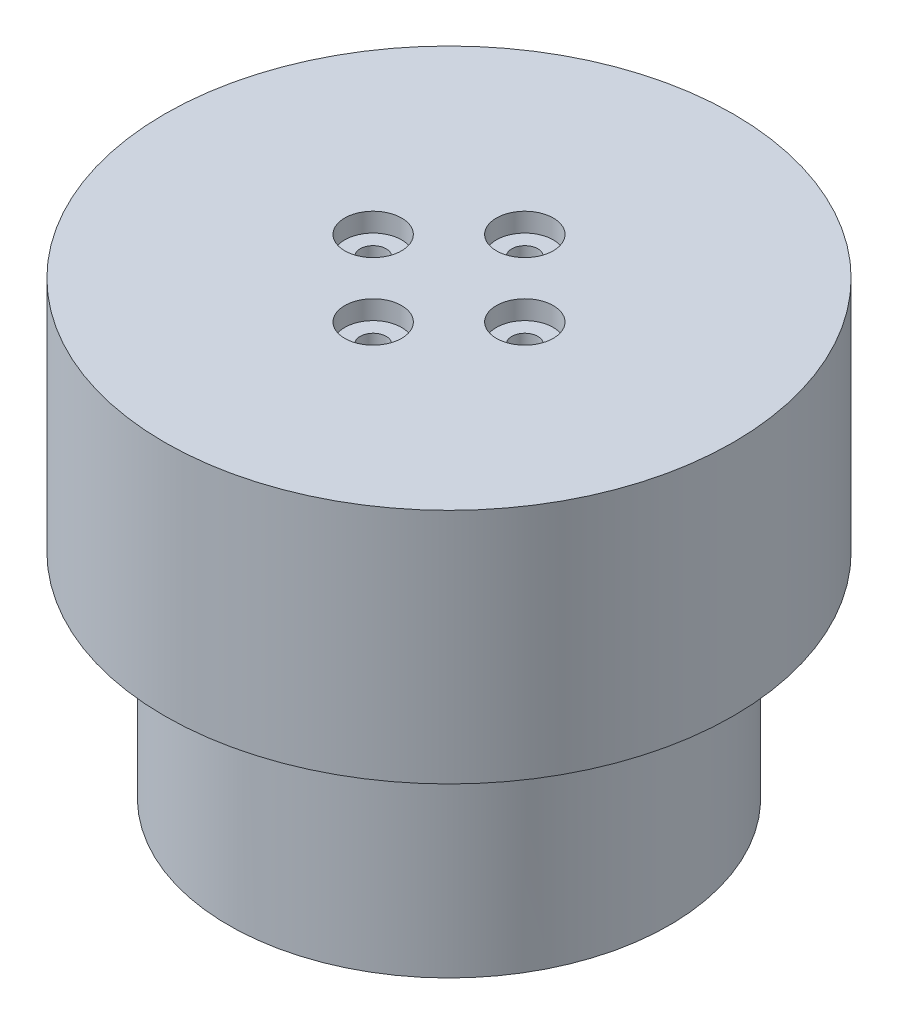
SolidWorks part; units mm, degrees
ref_plane "Plan de face" through (0, 0, 0) normal (0, 0, 1) x (1, 0, 0)
ref_plane "Plan de dessus" through (0, 0, 0) normal (0, 1, 0) x (1, 0, 0)
ref_plane "Plan de droite" through (0, 0, 0) normal (1, 0, 0) x (0, 0, -1)
sketch "Esquisse1" plane through (0, 0, 0) normal (0, 1, 0) x (1, 0, 0)
  circle A0 centre (0, 0) radius 47.75
  dimension "D1" = 95.5
extrude "Boss.-Extru.1" add sketch "Esquisse1" along normal blind 50
sketch "Esquisse2" plane through (0, 0, 0) normal (0, -1, 0) x (-1, 0, 0)
  circle A0 centre (0, 0) radius 26
extrude "Enlèv. mat.-Extru.1" cut sketch "Esquisse2" against normal blind 20
sketch "Esquisse3" plane through (0, 20, 0) normal (0, -1, 0) x (-1, 0, 0)
  circle A0 centre (0, 0) radius 11
  dimension "D1" = 22
extrude "Enlèv. mat.-Extru.5" cut sketch "Esquisse3" against normal blind 7.5
sketch "Esquisse4" plane through (0, 27.5, 0) normal (0, -1, 0) x (-1, 0, 0)
  circle A0 centre (0, 0) radius 5
  dimension "D1" = 10
extrude "Enlèv. mat.-Extru.6" cut sketch "Esquisse4" against normal blind 13.5
sketch "Esquisse5" plane through (0, 50, 0) normal (0, 1, 0) x (1, 0, 0)
  line L0 (-26, 0) -> (26, 0)
  line L1 (0, 26) -> (0, -26)
  circle A0 centre (0, 0) radius 26
  point P8 (-16, 0)
  point P9 (0, 16)
  point P10 (16, 0)
  point P11 (0, -16)
  dimension "D1" = 52
sketch "Esquisse11" plane through (0, 50, 0) normal (0, 1, 0) x (1, 0, 0)
  circle A0 centre (-16, 0) radius 2.75
  circle A1 centre (0, 16) radius 2.75
  circle A2 centre (16, 0) radius 2.75
  circle A3 centre (0, -16) radius 2.75
  dimension "D1" = 5.5
  dimension "D2" = 5.5
  dimension "D3" = 5.5
  dimension "D4" = 5.5
extrude "Enlèv. mat.-Extru.11" cut sketch "Esquisse11" against normal through all
ref_plane "Plan1" through (-47.75, 0, 0) normal (-1, 0, 0) x (0, 0, 1)
ref_plane "Plan2" through (47.75, 0, 0) normal (1, 0, 0) x (0, 0, -1)
sketch "Esquisse12" plane through (0, 0, 0) normal (0, -1, 0) x (1, 0, 0)
  circle A0 centre (0, 0) radius 46.5
  circle M2 centre (0, 0) radius 47.75
extrude "Enlèv. mat.-Extru.12" cut sketch "Esquisse12" against normal through all contours A0 M2
ref_plane "Plan3" through (0, 45, 0) normal (0, 1, 0) x (1, 0, 0)
other "Enlèv. mat.-Surface1"
sketch "Esquisse16" plane through (0, 45, 0) normal (0, 1, 0) x (1, 0, 0)
  circle A0 centre (0, 0) radius 60
extrude "Boss.-Extru.3" add sketch "Esquisse16" along normal blind 50 contours A0
sketch "Esquisse17" plane through (0, 95, 0) normal (0, 1, 0) x (1, 0, 0)
  circle A0 centre (0, -16) radius 2.75 construction
  circle A1 centre (-16, 0) radius 2.75 construction
  circle A2 centre (0, 16) radius 2.75 construction
  circle A3 centre (16, 0) radius 2.75 construction
  circle A4 centre (0, -16) radius 2.75
  circle A5 centre (-16, 0) radius 2.75
  circle A6 centre (0, 16) radius 2.75
  circle A7 centre (16, 0) radius 2.75
extrude "Enlèv. mat.-Extru.14" cut sketch "Esquisse17" against normal through all
sketch "Esquisse18" plane through (0, 95, 0) normal (0, 1, 0) x (1, 0, 0)
  circle A0 centre (0, 16) radius 6
  circle A1 centre (16, 0) radius 6
  circle A2 centre (0, -16) radius 6
  circle A3 centre (-16, 0) radius 6
  dimension "D1" = 12
  dimension "D2" = 12
  dimension "D3" = 12
  dimension "D4" = 12
extrude "Enlèv. mat.-Extru.15" cut sketch "Esquisse18" against normal blind 4
